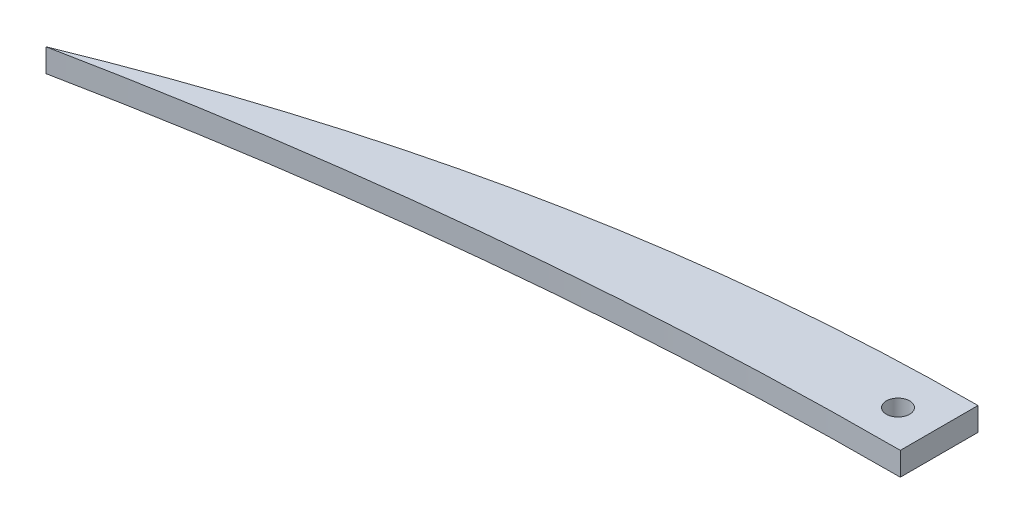
SolidWorks part; units mm, degrees
ref_plane "Front Plane" through (0, 0, 0) normal (0, 0, 1) x (1, 0, 0)
ref_plane "Top Plane" through (0, 0, 0) normal (0, 1, 0) x (1, 0, 0)
ref_plane "Right Plane" through (0, 0, 0) normal (1, 0, 0) x (0, 0, -1)
sketch "Sketch1" plane through (0, 0, 0) normal (0, 1, 0) x (1, 0, 0)
  line L1 (0, 0) -> (100, 0)
  line L2 (0, 0) -> (0, 20)
  line L3 (0, 20) -> (100, 20)
  line L4 (100, 0) -> (100, 20)
  spline S0 degree 2 poles (0, 0) (49.0098, 20) (100, 20) knots 0 0 0 1 1 1
  spline S1 degree 2 poles (0, 0) (49.7506, 10) (100, 10) knots 0 0 0 1 1 1
  dimension "D1" = 100
  dimension "D2" = 20
  dimension "D3" = 10
extrude "Boss-Extrude1" add sketch "Sketch1" along normal blind 3 contours S0 S1 L4
sketch "Sketch2" plane through (0, 3, 0) normal (0, 1, 0) x (1, 0, 0)
  circle A0 centre (95.0803, 14.6175) radius 1.5
extrude "Cut-Extrude1" cut sketch "Sketch2" against normal blind 3
